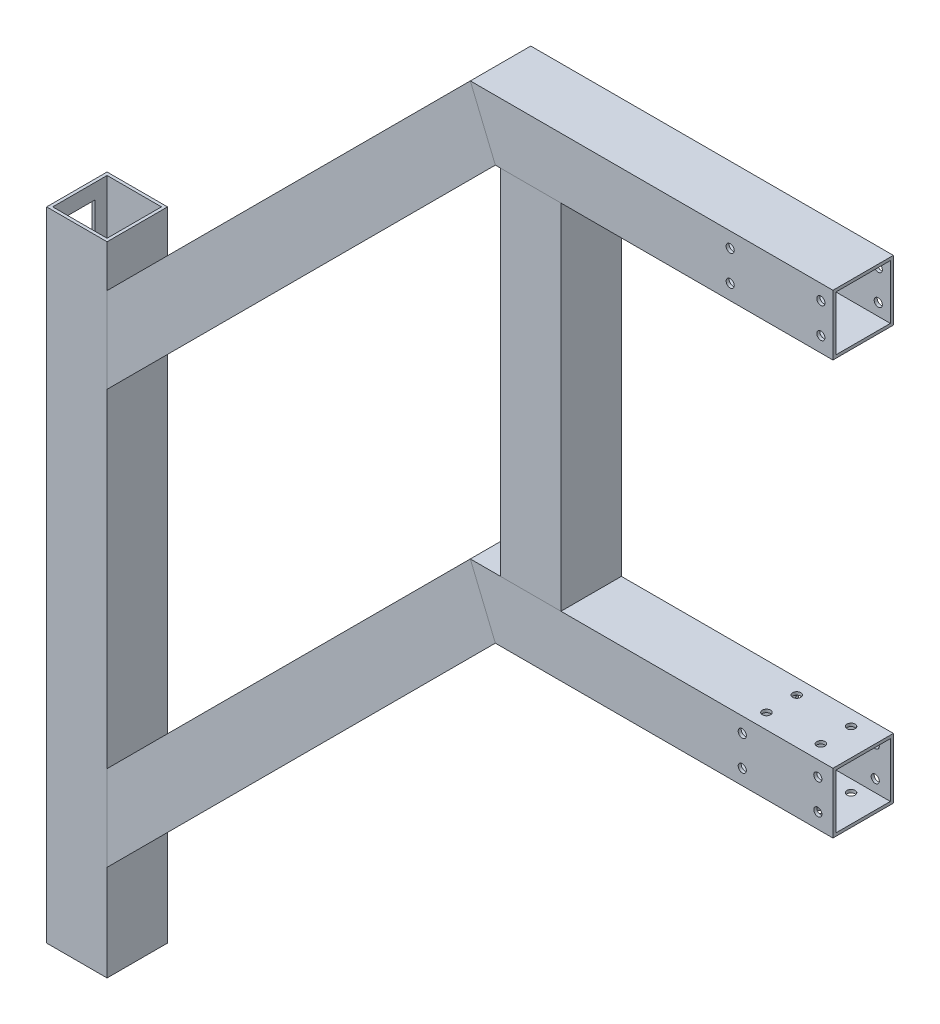
SolidWorks part; units mm, degrees
material "6061 合金"
ref_plane "前视基准面" through (0, 0, 0) normal (0, 0, 1) x (1, 0, 0)
ref_plane "上视基准面" through (0, 0, 0) normal (0, 1, 0) x (1, 0, 0)
ref_plane "右视基准面" through (0, 0, 0) normal (1, 0, 0) x (0, 0, -1)
sketch "草图1" plane through (0, 0, 0) normal (0, 0, 1) x (1, 0, 0)
  line L0 (260.2051, 277.2051) -> (140.2051, 277.2051)
  line L1 (140.2051, 277.2051) -> (0, 137)
  line L2 (260.2051, 140.2051) -> (140.2051, 140.2051)
  line L3 (140.2051, 140.2051) -> (0, 0)
  line L4 (0, 171) -> (0, -40)
  line L5 (150.2051, 277.2051) -> (150.2051, 140.2051)
  point P11 (0, 0)
  point P12 (0, 0)
  dimension "D1" = 120
  dimension "D2" = 137
  dimension "D3" = 45
  dimension "D4" = 34
  dimension "D5" = 40
  dimension "D6" = 110
  dimension "D7" = 198.28
  dimension "D8" = 211
  dimension "D9" = 260.2051
other "方形管 20 X 20 X 2(1)"
ref_plane "基准面1" through (260.2051, 277.2051, 0) normal (-1, 0, 0) x (0, -1, 0)
sketch "Sketch1" plane through (260.2051, 277.2051, 0) normal (-1, 0, 0) x (0, -1, 0)
  line L0 (19, 9) -> (19, -9)
  line L1 (20, 10) -> (0, 10)
  line L2 (20, 10) -> (20, -10)
  line L3 (20, -10) -> (0, -10)
  line L4 (0, 10) -> (0, -10)
  line L5 (10, -10) -> (10, 10) construction
  line L6 (20, 0) -> (0, 0) construction
  line L7 (19, -9) -> (1, -9)
  line L8 (1, 9) -> (1, -9)
  line L9 (19, 9) -> (1, 9)
  point P0 (10, 0)
  point P4 (0, 0)
  point P9 (0, 0)
  point P10 (0, 0)
  point P33 (0, 0)
  dimension "D1" = 20
  dimension "D2" = 1
sketch "草图3" plane through (0, 0, 10) normal (0, 0, 1) x (1, 0, 0)
  line L0 (241.2051, 277.2051) -> (241.2051, 257.2051) construction
  line L1 (140.2051, 277.2051) -> (260.2051, 277.2051) construction
  line L2 (148.4894, 257.2051) -> (260.2051, 257.2051) construction
  line L3 (241.2051, 267.2051) -> (260.2051, 267.2051) construction
  line L4 (260.2051, 257.2051) -> (260.2051, 277.2051) construction
  line L5 (242.7051, 130.2051) -> (260.2051, 130.2051) construction
  line L6 (260.2051, 120.2051) -> (260.2051, 140.2051) construction
  line L7 (242.7051, 130.2051) -> (242.7051, 120.2051) construction
  line L8 (148.4894, 120.2051) -> (260.2051, 120.2051) construction
  circle A0 centre (256.2051, 272.2051) radius 1.35
  circle A1 centre (226.2051, 272.2051) radius 1.35
  circle A2 centre (226.2051, 262.2051) radius 1.35
  circle A3 centre (256.2051, 262.2051) radius 1.35
  circle A4 centre (255.2051, 135.2051) radius 1.35
  circle A5 centre (255.2051, 125.2051) radius 1.35
  circle A6 centre (230.2051, 125.2051) radius 1.35
  circle A7 centre (230.2051, 135.2051) radius 1.35
  dimension "D4" = 2.7
  dimension "D1" = 4
  dimension "D2" = 10
  dimension "D3" = 30
  dimension "D5" = 5
  dimension "D6" = 25
  dimension "D7" = 10
extrude "切除-拉伸1" cut sketch "草图3" against normal through all
sketch "草图4" plane through (0, 120.2051, 0) normal (0, -1, 0) x (1, 0, 0)
  line L0 (242.2051, 10) -> (242.2051, 0) construction
  line L1 (148.4894, 10) -> (260.2051, 10) construction
  line L2 (242.2051, 0) -> (260.2051, 0) construction
  line L3 (260.2051, -10) -> (260.2051, 10) construction
  circle A0 centre (251.2051, 5) radius 1.35
  circle A1 centre (233.2051, 5) radius 1.35
  circle A2 centre (233.2051, -5) radius 1.35
  circle A3 centre (251.2051, -5) radius 1.35
  dimension "D4" = 2.7
  dimension "D1" = 10
  dimension "D2" = 18
  dimension "D3" = 9
extrude "切除-拉伸2" cut sketch "草图4" against normal up to surface (20 mm away) up to face at (200.2051, 140.2051, 0)
sketch "草图5" plane through (0, 0, 0) normal (-1, 0, 0) x (0, 0, 1)
  line L0 (10, -40) -> (-10, -40) construction
  line L1 (-5, -35) -> (5, -35)
  line L2 (-5, -35) -> (-5, -15)
  line L3 (-5, -15) -> (5, -15)
  line L4 (5, -35) -> (5, -15)
  line L5 (0, -15) -> (0, -35) construction
  line L6 (-5, -25) -> (5, -25) construction
  line L7 (0, -40) -> (0, 0) construction
  line L8 (-10, 65.5) -> (10, 65.5) construction
  line L9 (-10, -40) -> (-10, 171) construction
  line L10 (-5, 146) -> (5, 146)
  line L11 (5, 166) -> (5, 146)
  line L12 (-5, 166) -> (5, 166)
  line L13 (-5, 166) -> (-5, 146)
  line L14 (10, -40) -> (10, 171) construction
  point P0 (0, -25)
  dimension "D1" = 5
  dimension "D2" = 10
  dimension "D3" = 20
extrude "切除-拉伸3" cut sketch "草图5" against normal up to next (1 mm away)
move or copy body "实体-移动/复制1" [suppressed] bodies to move or copy 107 109 110 112 114 116
